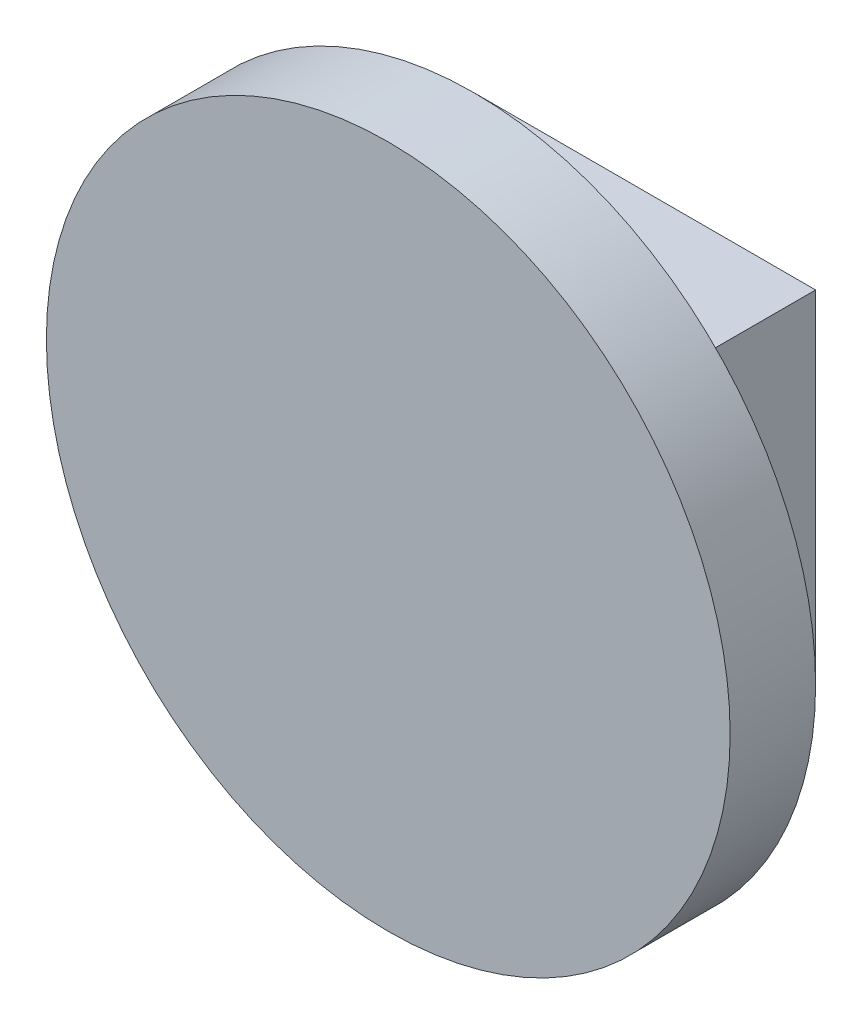
SolidWorks part; units mm, degrees
ref_plane "Front Plane" through (0, 0, 0) normal (0, 0, 1) x (1, 0, 0)
ref_plane "Top Plane" through (0, 0, 0) normal (0, 1, 0) x (1, 0, 0)
ref_plane "Right Plane" through (0, 0, 0) normal (1, 0, 0) x (0, 0, -1)
sketch "Sketch2" plane through (0, 0, 0) normal (0, 0, 1) x (1, 0, 0)
  circle A0 centre (0, 0) radius 6.35
  dimension "D1" = 12.7
extrude "Boss-Extrude1" add sketch "Sketch2" along normal blind 1.5875
sketch "Sketch3" plane through (0, 0, 0) normal (0, 0, -1) x (-1, 0, 0)
  line L1 (-1.5875, -1.5875) -> (1.5875, -1.5875)
  line L2 (-1.5875, -1.5875) -> (-1.5875, 1.5875)
  line L3 (-1.5875, 1.5875) -> (1.5875, 1.5875)
  line L4 (1.5875, -1.5875) -> (1.5875, 1.5875)
  line L5 (-1.5875, -1.5875) -> (1.5875, 1.5875) construction
  line L6 (-1.5875, 1.5875) -> (1.5875, -1.5875) construction
  line L7 (-3.175, -3.175) -> (3.175, -3.175)
  line L8 (-3.175, -3.175) -> (-3.175, 3.175)
  line L9 (-3.175, 3.175) -> (3.175, 3.175)
  line L10 (3.175, -3.175) -> (3.175, 3.175)
  line L11 (-3.175, -3.175) -> (3.175, 3.175) construction
  line L12 (-3.175, 3.175) -> (3.175, -3.175) construction
  point P0 (0, 0)
  point P6 (0, 0)
  dimension "D1" = 3.175
  dimension "D2" = 3.175
  dimension "D3" = 1.5875
  dimension "D4" = 1.5875
extrude "Boss-Extrude2" add sketch "Sketch3" along normal blind 3.175
